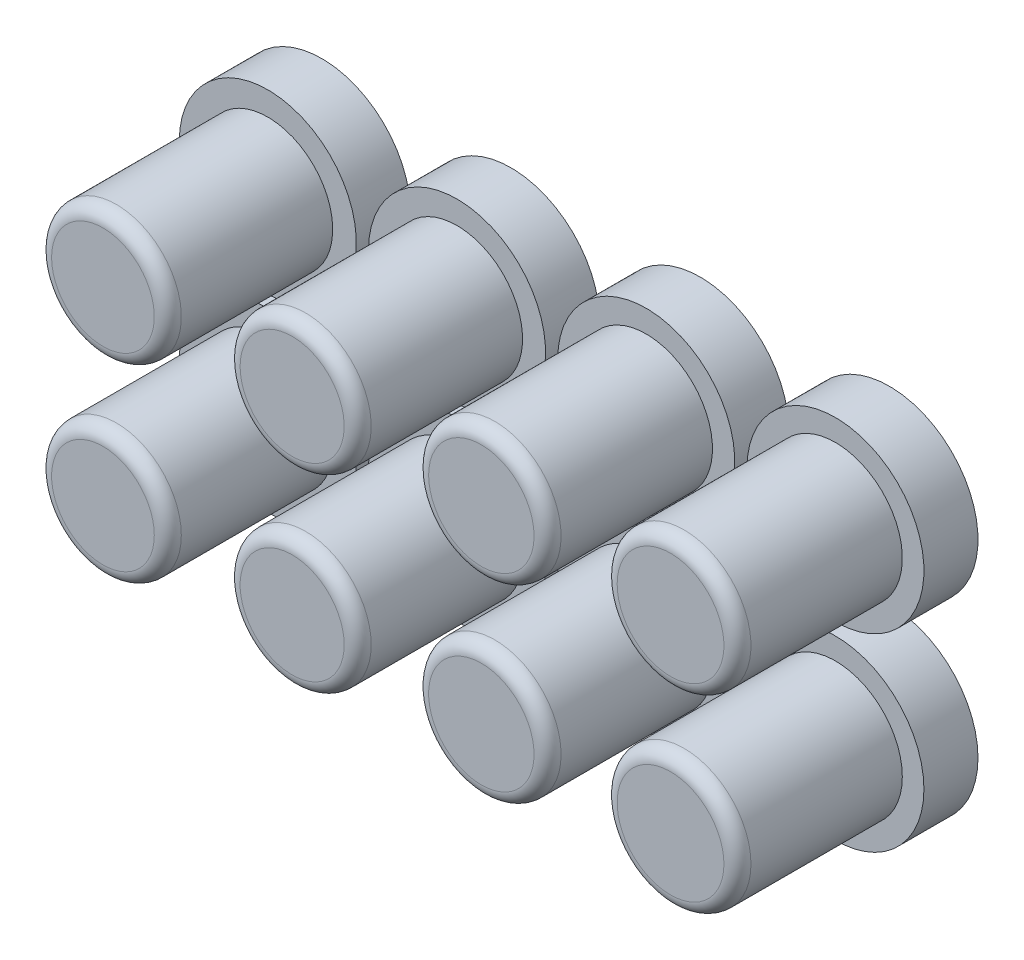
SolidWorks part; units mm, degrees
ref_plane "Ebene vorne" through (0, 0, 0) normal (0, 0, 1) x (1, 0, 0)
ref_plane "Ebene oben" through (0, 0, 0) normal (0, 1, 0) x (1, 0, 0)
ref_plane "Ebene rechts" through (0, 0, 0) normal (1, 0, 0) x (0, 0, -1)
sketch "Sketch1" plane through (0, 0, 0) normal (0, 0, 1) x (1, 0, 0)
  line L0 (55, 0) -> (-55, 0) construction
  circle A4 centre (-10.5, -3.5) radius 2.4
  circle A5 centre (-3.5, -3.5) radius 2.425
  circle A6 centre (3.5, -3.5) radius 2.45
  circle A7 centre (10.5, -3.5) radius 2.475
  circle A8 centre (10.5, 3.5) radius 2.475
  circle A9 centre (3.5, 3.5) radius 2.45
  circle A10 centre (-3.5, 3.5) radius 2.425
  circle A11 centre (-10.5, 3.5) radius 2.4
  dimension "D1" = 4.8
  dimension "D2" = 4.85
  dimension "D3" = 4.9
  dimension "D4" = 4.95
  dimension "D5" = 7
  dimension "D6" = 7
  dimension "D7" = 7
  dimension "D8" = 0
  dimension "D9" = 0
  dimension "D10" = 0
  dimension "D11" = 3.5
  dimension "D12" = 3.5
sketch "Sketch4" plane through (0, 0, 0) normal (0, 0, 1) x (1, 0, 0)
  line L0 (55, 0) -> (-55, 0) construction
  circle A0 centre (-10.5, -3.5) radius 3.275
  circle A1 centre (-3.5, -3.5) radius 3.275
  circle A2 centre (3.5, -3.5) radius 3.275
  circle A3 centre (10.5, -3.5) radius 3.275
  circle A4 centre (-10.5, 3.5) radius 3.275
  circle A5 centre (-3.5, 3.5) radius 3.275
  circle A6 centre (3.5, 3.5) radius 3.275
  circle A7 centre (10.5, 3.5) radius 3.275
  dimension "D1" = 6.55
  dimension "D2" = 6.55
  dimension "D3" = 6.55
  dimension "D4" = 6.55
extrude "Boss-Extrude4" add sketch "Sketch4" against normal blind 2
extrude "Boss-Extrude5" add sketch "Sketch1" along normal blind 6.1
sketch "Sketch6" plane through (0, 0, 0) normal (0, 0, 1) x (1, 0, 0)
  text T0 "4.95      4.9      4.85       4.8" font "Century Gothic" height 1.5
extrude "Cut-Extrude1" cut sketch "Sketch6" against normal blind 6.1 from offset 1.8 offset against normal yes
fillet "Fillet1" radius 0.5 1 edges at (-8.1, -3.5, 6.1)
fillet "Fillet2" radius 0.5 1 edges at (-1.075, -3.5, 6.1)
fillet "Fillet3" radius 0.5 1 edges at (5.95, -3.5, 6.1)
fillet "Fillet4" radius 0.5 1 edges at (12.975, -3.5, 6.1)
fillet "Fillet5" radius 0.5 1 edges at (8.025, 3.5, 6.1)
fillet "Fillet6" radius 0.5 1 edges at (1.05, 3.5, 6.1)
fillet "Fillet7" radius 0.5 1 edges at (-5.925, 3.5, 6.1)
fillet "Fillet8" radius 0.5 1 edges at (-12.9, 3.5, 6.1)
sketch "Sketch7" plane through (0, 0, 0) normal (0, 0, 1) x (1, 0, 0)
  text T0 "4.95      4.9      4.85      4.8" font "Century Gothic" height 1.5
extrude "Cut-Extrude2" cut sketch "Sketch7" against normal blind 1 from offset 1.8
